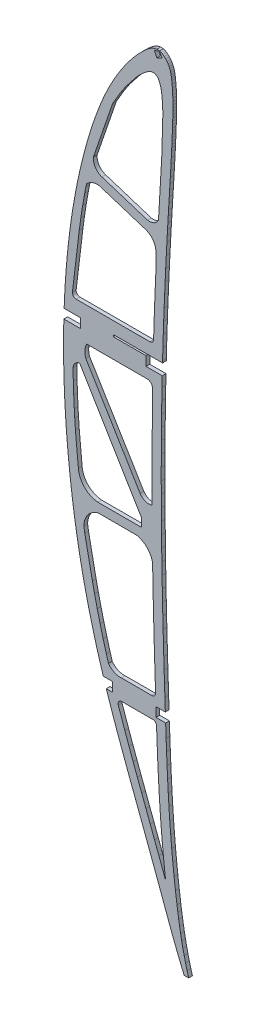
SolidWorks part; units mm, degrees
ref_plane "前视基准面" through (0, 0, 0) normal (0, 0, 1) x (1, 0, 0)
ref_plane "上视基准面" through (0, 0, 0) normal (0, 1, 0) x (1, 0, 0)
ref_plane "右视基准面" through (0, 0, 0) normal (1, 0, 0) x (0, 0, -1)
sketch "Model" plane through (0, 0, 0) normal (0, 0, 1) x (1, 0, 0)
  line L0 (90.473, 1.4161) -> (89.2536, 4.2882)
  line L1 (89.2536, 4.2882) -> (87.9798, 7.3505)
  line L2 (87.9798, 7.3505) -> (86.7325, 10.425)
  line L3 (86.7325, 10.425) -> (85.5328, 13.4636)
  line L4 (85.5328, 13.4636) -> (84.3598, 16.5103)
  line L5 (84.3598, 16.5103) -> (83.2074, 19.565)
  line L6 (83.2074, 19.565) -> (82.0699, 22.6253)
  line L7 (82.0699, 22.6253) -> (80.9421, 25.69)
  line L8 (80.9421, 25.69) -> (78.6963, 31.8259)
  line L9 (78.6963, 31.8259) -> (76.4399, 37.9543)
  line L10 (76.4399, 37.9543) -> (74.1677, 44.075)
  line L11 (74.1677, 44.075) -> (71.8829, 50.1892)
  line L12 (71.8829, 50.1892) -> (69.5892, 56.2989)
  line L13 (69.5892, 56.2989) -> (67.2905, 62.4075)
  line L14 (67.2905, 62.4075) -> (64.9878, 68.5169)
  line L15 (64.9878, 68.5169) -> (62.687, 74.6293)
  line L16 (62.687, 74.6293) -> (60.4035, 80.7125)
  line L17 (60.4035, 80.7125) -> (58.1378, 86.8005)
  line L18 (58.1378, 86.8005) -> (55.8997, 92.8976)
  line L19 (55.8997, 92.8976) -> (53.7021, 99.0086)
  line L20 (53.7021, 99.0086) -> (51.5567, 105.1368)
  line L21 (51.5567, 105.1368) -> (48.7789, 113.4293)
  line L22 (47.169, 118.4293) -> (45.5864, 123.5389)
  line L23 (45.5864, 123.5389) -> (43.7907, 129.6364)
  line L24 (43.7907, 129.6364) -> (42.081, 135.7577)
  line L25 (42.081, 135.7577) -> (40.4605, 141.9028)
  line L26 (40.4605, 141.9028) -> (38.9279, 148.0709)
  line L27 (38.9279, 148.0709) -> (37.4875, 154.2619)
  line L28 (37.4875, 154.2619) -> (36.1382, 160.475)
  line L29 (36.1382, 160.475) -> (34.9017, 166.6049)
  line L30 (34.9017, 166.6049) -> (33.7535, 172.7496)
  line L31 (33.7535, 172.7496) -> (32.6908, 178.9101)
  line L32 (32.6908, 178.9101) -> (31.7116, 185.0833)
  line L33 (31.7116, 185.0833) -> (30.8129, 191.269)
  line L34 (30.8129, 191.269) -> (29.9918, 197.4671)
  line L35 (29.9918, 197.4671) -> (29.2462, 203.6765)
  line L36 (29.2462, 203.6765) -> (28.5771, 209.8562)
  line L37 (28.5771, 209.8562) -> (27.9817, 216.0411)
  line L38 (27.9817, 216.0411) -> (27.4592, 222.2302)
  line L39 (27.4592, 222.2302) -> (27.0106, 228.4255)
  line L40 (27.0106, 228.4255) -> (26.6368, 234.6261)
  line L41 (26.6368, 234.6261) -> (26.3398, 240.8321)
  line L42 (26.3398, 240.8321) -> (26.1187, 247.0423)
  line L43 (26.1187, 247.0423) -> (25.9752, 253.264)
  line L44 (25.9752, 253.264) -> (25.9097, 259.485)
  line L45 (25.9097, 259.485) -> (25.9264, 265.7057)
  line L46 (25.9264, 265.7057) -> (26.0242, 271.9249)
  line L47 (26.0242, 271.9249) -> (26.0682, 273.4293)
  line L48 (26.2185, 278.4293) -> (26.4742, 284.3603)
  line L49 (26.4742, 284.3603) -> (26.8295, 290.5758)
  line L50 (26.8295, 290.5758) -> (27.2798, 296.8594)
  line L51 (27.2798, 296.8594) -> (27.8256, 303.1352)
  line L52 (27.8256, 303.1352) -> (28.4699, 309.3992)
  line L53 (28.4699, 309.3992) -> (29.219, 315.6509)
  line L54 (29.219, 315.6509) -> (30.0758, 321.8872)
  line L55 (30.0758, 321.8872) -> (31.0464, 328.1074)
  line L56 (31.0464, 328.1074) -> (32.1349, 334.3098)
  line L57 (32.1349, 334.3098) -> (32.7366, 337.4701)
  line L58 (32.7366, 337.4701) -> (33.3707, 340.6227)
  line L59 (33.3707, 340.6227) -> (34.0381, 343.7678)
  line L60 (34.0381, 343.7678) -> (34.7369, 346.9063)
  line L61 (34.7369, 346.9063) -> (35.47, 350.0362)
  line L62 (35.47, 350.0362) -> (36.2365, 353.1597)
  line L63 (36.2365, 353.1597) -> (37.0384, 356.2756)
  line L64 (37.0384, 356.2756) -> (37.8971, 359.4651)
  line L65 (37.8971, 359.4651) -> (38.7943, 362.6432)
  line L66 (38.7943, 362.6432) -> (39.7331, 365.8092)
  line L67 (39.7331, 365.8092) -> (40.7155, 368.9621)
  line L68 (40.7155, 368.9621) -> (41.7446, 372.0999)
  line L69 (41.7446, 372.0999) -> (42.8225, 375.2219)
  line L70 (42.8225, 375.2219) -> (43.952, 378.3282)
  line L71 (43.952, 378.3282) -> (44.5597, 379.9322)
  line L72 (44.5597, 379.9322) -> (45.1815, 381.5308)
  line L73 (45.1815, 381.5308) -> (45.8197, 383.1222)
  line L74 (45.8197, 383.1222) -> (46.4752, 384.7063)
  line L75 (46.4752, 384.7063) -> (47.1482, 386.2811)
  line L76 (47.1482, 386.2811) -> (47.8385, 387.8477)
  line L77 (47.8385, 387.8477) -> (48.5493, 389.4042)
  line L78 (48.5493, 389.4042) -> (49.3153, 391.0262)
  line L79 (49.3153, 391.0262) -> (50.1038, 392.6361)
  line L80 (50.1038, 392.6361) -> (50.9168, 394.2361)
  line L81 (50.9168, 394.2361) -> (51.7533, 395.8241)
  line L82 (51.7533, 395.8241) -> (52.6142, 397.4041)
  line L83 (52.6142, 397.4041) -> (53.5026, 398.9744)
  line L84 (53.5026, 398.9744) -> (54.4183, 400.5368)
  line L85 (54.4183, 400.5368) -> (55.4371, 402.2139)
  line L86 (55.4371, 402.2139) -> (56.4875, 403.8773)
  line L87 (56.4875, 403.8773) -> (57.565, 405.5178)
  line L88 (57.565, 405.5178) -> (58.6677, 407.1315)
  line L89 (58.6677, 407.1315) -> (59.7948, 408.7121)
  line L90 (59.7948, 408.7121) -> (60.9427, 410.2527)
  line L91 (60.9427, 410.2527) -> (62.1106, 411.748)
  line L92 (62.1106, 411.748) -> (62.8372, 412.6426)
  line L93 (62.8372, 412.6426) -> (63.5775, 413.5247)
  line L94 (63.5775, 413.5247) -> (64.336, 414.3996)
  line L95 (64.336, 414.3996) -> (65.1196, 415.2756)
  line L96 (65.1196, 415.2756) -> (65.9348, 416.159)
  line L97 (65.9348, 416.159) -> (66.7875, 417.0561)
  line L98 (66.7875, 417.0561) -> (67.6853, 417.9731)
  line L99 (67.6853, 417.9731) -> (68.9368, 419.2049)
  line L100 (68.9368, 419.2049) -> (70.2576, 420.4066)
  line L101 (70.2576, 420.4066) -> (71.6302, 421.5015)
  line L102 (71.6302, 421.5015) -> (73.0377, 422.4138)
  line L103 (73.0377, 422.4138) -> (74.4616, 423.0665)
  line L104 (74.4616, 423.0665) -> (75.8862, 423.383)
  line L105 (75.8862, 423.383) -> (77.2927, 423.2862)
  line L106 (77.2927, 423.2862) -> (78.1436, 422.9933)
  line L107 (78.1436, 422.9933) -> (78.1545, 422.9896)
  line L108 (78.1545, 422.9896) -> (78.9905, 422.5256)
  line L109 (78.9905, 422.5256) -> (79.7866, 421.9227)
  line L110 (79.7866, 421.9227) -> (80.5307, 421.2035)
  line L111 (80.5307, 421.2035) -> (81.2106, 420.3954)
  line L112 (81.2106, 420.3954) -> (81.8132, 419.5228)
  line L113 (81.8132, 419.5228) -> (82.3264, 418.6124)
  line L114 (82.3264, 418.6124) -> (82.6997, 417.7879)
  line L115 (82.6997, 417.7879) -> (83.0023, 416.9553)
  line L116 (83.0023, 416.9553) -> (83.2442, 416.115)
  line L117 (83.2442, 416.115) -> (83.4364, 415.2676)
  line L118 (83.4364, 415.2676) -> (83.5887, 414.4144)
  line L119 (83.5887, 414.4144) -> (83.7122, 413.557)
  line L120 (83.7122, 413.557) -> (83.8159, 412.6957)
  line L121 (83.8159, 412.6957) -> (83.9762, 411.1562)
  line L122 (83.9762, 411.1562) -> (84.1087, 409.6125)
  line L123 (84.1087, 409.6125) -> (84.2163, 408.0638)
  line L124 (84.2163, 408.0638) -> (84.2991, 406.5119)
  line L125 (84.2991, 406.5119) -> (84.36, 404.9571)
  line L126 (84.36, 404.9571) -> (84.3999, 403.4013)
  line L127 (84.3999, 403.4013) -> (84.4207, 401.8468)
  line L128 (84.4207, 401.8468) -> (84.4237, 400.2884)
  line L129 (84.4237, 400.2884) -> (84.4105, 398.7323)
  line L130 (84.4105, 398.7323) -> (84.3833, 397.1777)
  line L131 (84.3833, 397.1777) -> (84.3451, 395.6225)
  line L132 (84.3451, 395.6225) -> (84.2988, 394.069)
  line L133 (84.2988, 394.069) -> (84.2456, 392.5152)
  line L134 (84.2456, 392.5152) -> (84.1873, 390.9602)
  line L135 (84.1873, 390.9602) -> (84.1282, 389.4032)
  line L136 (84.1282, 389.4032) -> (84.066, 387.847)
  line L137 (84.066, 387.847) -> (84.0018, 386.2907)
  line L138 (84.0018, 386.2907) -> (83.9357, 384.7343)
  line L139 (83.9357, 384.7343) -> (83.8665, 383.1778)
  line L140 (83.8665, 383.1778) -> (83.7943, 381.6212)
  line L141 (83.7943, 381.6212) -> (83.7202, 380.0645)
  line L142 (83.7202, 380.0645) -> (83.562, 376.9476)
  line L143 (83.562, 376.9476) -> (83.3927, 373.8313)
  line L144 (83.3927, 373.8313) -> (83.2164, 370.7166)
  line L145 (83.2164, 370.7166) -> (83.0321, 367.6026)
  line L146 (83.0321, 367.6026) -> (82.8447, 364.4885)
  line L147 (82.8447, 364.4885) -> (82.6544, 361.3742)
  line L148 (82.6544, 361.3742) -> (82.4641, 358.2589)
  line L149 (82.4641, 358.2589) -> (82.2749, 355.1427)
  line L150 (82.2749, 355.1427) -> (82.0876, 352.0276)
  line L151 (82.0876, 352.0276) -> (81.9022, 348.9135)
  line L152 (81.9022, 348.9135) -> (81.7209, 345.7986)
  line L153 (81.7209, 345.7986) -> (81.5416, 342.6839)
  line L154 (81.5416, 342.6839) -> (81.3663, 339.5683)
  line L155 (81.3663, 339.5683) -> (81.1941, 336.4518)
  line L156 (81.1941, 336.4518) -> (80.8634, 330.2254)
  line L157 (80.8634, 330.2254) -> (80.5506, 324.0009)
  line L158 (80.5506, 324.0009) -> (80.2548, 317.776)
  line L159 (80.2548, 317.776) -> (79.9771, 311.551)
  line L160 (79.9771, 311.551) -> (79.7175, 305.3237)
  line L161 (79.7175, 305.3237) -> (79.4779, 299.0954)
  line L162 (79.4779, 299.0954) -> (79.2585, 292.8649)
  line L163 (79.2585, 292.8649) -> (79.0597, 286.6443)
  line L164 (79.0597, 286.6443) -> (78.8818, 280.4246)
  line L165 (78.8818, 280.4246) -> (78.8564, 279.4293)
  line L166 (78.7057, 273.4293) -> (78.5851, 267.9858)
  line L167 (78.5851, 267.9858) -> (78.4673, 261.7657)
  line L168 (78.4673, 261.7657) -> (78.3696, 255.5436)
  line L169 (78.3696, 255.5436) -> (78.292, 249.3203)
  line L170 (78.292, 249.3203) -> (78.2341, 243.1038)
  line L171 (78.2341, 243.1038) -> (78.1961, 236.8892)
  line L172 (78.1961, 236.8892) -> (78.1771, 230.6755)
  line L173 (78.1771, 230.6755) -> (78.1751, 224.4625)
  line L174 (78.1751, 224.4625) -> (78.1912, 218.2483)
  line L175 (78.1912, 218.2483) -> (78.2233, 212.0338)
  line L176 (78.2233, 212.0338) -> (78.2715, 205.817)
  line L177 (78.2715, 205.817) -> (78.3346, 199.6048)
  line L178 (78.3346, 199.6048) -> (78.4125, 193.3943)
  line L179 (78.4125, 193.3943) -> (78.5045, 187.1844)
  line L180 (78.5045, 187.1844) -> (78.6114, 180.9761)
  line L181 (78.6114, 180.9761) -> (78.7323, 174.7675)
  line L182 (78.7323, 174.7675) -> (78.8663, 168.5574)
  line L183 (78.8663, 168.5574) -> (79.0144, 162.347)
  line L184 (79.0144, 162.347) -> (79.1754, 156.1381)
  line L185 (79.1754, 156.1381) -> (79.3482, 149.9317)
  line L186 (79.3482, 149.9317) -> (79.5311, 143.7268)
  line L187 (79.5311, 143.7268) -> (79.7239, 137.5213)
  line L188 (79.7239, 137.5213) -> (79.9228, 131.3171)
  line L189 (79.9228, 131.3171) -> (80.1297, 125.1102)
  line L190 (80.1297, 125.1102) -> (80.3571, 118.4293)
  line L191 (80.5289, 113.4293) -> (80.7816, 106.4889)
  line L192 (80.7816, 106.4889) -> (81.0244, 100.2856)
  line L193 (81.0244, 100.2856) -> (81.2912, 94.0833)
  line L194 (81.2912, 94.0833) -> (81.5889, 87.8834)
  line L195 (81.5889, 87.8834) -> (81.9236, 81.6841)
  line L196 (81.9236, 81.6841) -> (82.3043, 75.4858)
  line L197 (82.3043, 75.4858) -> (82.7354, 69.2817)
  line L198 (82.7354, 69.2817) -> (83.2212, 63.083)
  line L199 (83.2212, 63.083) -> (83.7659, 56.8899)
  line L200 (83.7659, 56.8899) -> (84.3733, 50.7025)
  line L201 (84.3733, 50.7025) -> (85.0457, 44.5199)
  line L202 (85.0457, 44.5199) -> (85.7878, 38.3434)
  line L203 (85.7878, 38.3434) -> (86.6038, 32.1711)
  line L204 (86.6038, 32.1711) -> (87.0437, 29.0654)
  line L205 (87.0437, 29.0654) -> (87.5093, 25.9657)
  line L206 (87.5093, 25.9657) -> (88.0068, 22.8715)
  line L207 (88.0068, 22.8715) -> (88.5429, 19.7849)
  line L208 (88.5429, 19.7849) -> (89.1227, 16.7073)
  line L209 (89.1227, 16.7073) -> (89.7531, 13.6409)
  line L210 (89.7531, 13.6409) -> (90.4399, 10.5869)
  line L211 (90.4399, 10.5869) -> (91.2028, 7.4882)
  line L212 (91.2028, 7.4882) -> (92.0221, 4.404)
  line L213 (92.0221, 4.404) -> (92.864, 1.4161)
  line L214 (92.864, 1.4161) -> (90.473, 1.4161)
  line L215 (75.3292, 320.7533) -> (75.0514, 314.5283)
  line L216 (75.0514, 314.5283) -> (74.7918, 308.301)
  line L217 (74.7918, 308.301) -> (74.5523, 302.0726)
  line L218 (74.5523, 302.0726) -> (74.3328, 295.8421)
  line L219 (74.3328, 295.8421) -> (74.134, 289.6216)
  line L220 (74.134, 289.6216) -> (74.0833, 287.8494)
  line L221 (72.0841, 285.9066) -> (32.6268, 285.9066)
  line L222 (30.641, 288.1445) -> (34.2933, 318.6281)
  line L223 (34.2933, 318.6281) -> (35.1501, 324.8644)
  line L224 (35.1501, 324.8644) -> (36.1207, 331.0847)
  line L225 (36.1207, 331.0847) -> (37.2092, 337.2871)
  line L226 (37.2092, 337.2871) -> (37.8109, 340.4473)
  line L227 (31.8893, 230.4372) -> (31.6368, 234.6261)
  line L228 (31.6368, 234.6261) -> (31.3398, 240.8321)
  line L229 (31.3398, 240.8321) -> (31.1187, 247.0423)
  line L230 (31.1187, 247.0423) -> (30.9752, 253.264)
  line L231 (57.1011, 111.6348) -> (73.6657, 111.6348)
  line L232 (75.6644, 109.7076) -> (75.7816, 106.4889)
  line L233 (75.7816, 106.4889) -> (76.0244, 100.2856)
  line L234 (76.0244, 100.2856) -> (76.2912, 94.0833)
  line L235 (76.2912, 94.0833) -> (76.5889, 87.8834)
  line L236 (76.5889, 87.8834) -> (76.9236, 81.6841)
  line L237 (76.9236, 81.6841) -> (77.3043, 75.4858)
  line L238 (77.3043, 75.4858) -> (77.7354, 69.2817)
  line L239 (77.7354, 69.2817) -> (78.2212, 63.083)
  line L240 (78.2212, 63.083) -> (78.7659, 56.8899)
  line L241 (78.7659, 56.8899) -> (79.3733, 50.7025)
  line L242 (79.3733, 50.7025) -> (80.0457, 44.5199)
  line L243 (80.0457, 44.5199) -> (80.5449, 40.3653)
  line L244 (80.5449, 40.3653) -> (79.1677, 44.075)
  line L245 (79.1677, 44.075) -> (76.8829, 50.1892)
  line L246 (76.8829, 50.1892) -> (74.5892, 56.2989)
  line L247 (74.5892, 56.2989) -> (72.2905, 62.4075)
  line L248 (72.2905, 62.4075) -> (69.9878, 68.5169)
  line L249 (69.9878, 68.5169) -> (67.687, 74.6293)
  line L250 (67.687, 74.6293) -> (65.4035, 80.7125)
  line L251 (65.4035, 80.7125) -> (63.1378, 86.8005)
  line L252 (63.1378, 86.8005) -> (60.8997, 92.8976)
  line L253 (60.8997, 92.8976) -> (58.7021, 99.0086)
  line L254 (58.7021, 99.0086) -> (55.2134, 108.974)
  line L255 (49.9336, 125.7554) -> (48.7907, 129.6364)
  line L256 (48.7907, 129.6364) -> (47.081, 135.7577)
  line L257 (47.081, 135.7577) -> (45.4605, 141.9028)
  line L258 (45.4605, 141.9028) -> (43.9279, 148.0709)
  line L259 (43.9279, 148.0709) -> (42.4875, 154.2619)
  line L260 (42.4875, 154.2619) -> (41.3223, 159.6277)
  line L261 (26.2185, 278.4293) -> (33.8514, 278.4293)
  line L262 (47.169, 118.4293) -> (52.169, 118.4293)
  line L263 (52.169, 118.4293) -> (52.169, 113.4293)
  line L264 (52.169, 113.4293) -> (48.7789, 113.4293)
  line L265 (75.3571, 118.4293) -> (75.3571, 113.4293)
  line L266 (75.3571, 118.4293) -> (80.3571, 118.4293)
  line L267 (80.5289, 113.4293) -> (75.3571, 113.4293)
  line L268 (70.057, 278.4293) -> (52.5208, 278.4293)
  line L269 (52.5208, 278.4293) -> (52.5208, 279.4293)
  line L270 (52.5208, 279.4293) -> (78.8564, 279.4293)
  line L271 (46.4432, 349.4196) -> (70.7733, 341.6607)
  line L272 (44.9904, 344.6799) -> (69.9353, 336.7249)
  line L273 (77.2787, 423.2659) -> (74.5538, 422.0128)
  line L274 (74.5538, 422.0128) -> (75.8059, 419.2879)
  line L275 (75.8059, 419.2879) -> (78.5318, 420.54)
  line L276 (78.5318, 420.54) -> (77.2787, 423.2659)
  line L277 (70.057, 273.4293) -> (70.057, 278.4293)
  line L278 (34.8514, 273.4293) -> (34.8514, 278.4293)
  line L279 (34.8514, 278.4293) -> (33.8514, 278.4293)
  line L280 (31.8893, 230.4372) -> (32.2643, 224.8927)
  line L282 (73.1408, 122.4795) -> (56.8453, 122.4795)
  line L283 (73.5404, 184.322) -> (73.6114, 180.9761)
  line L284 (73.6114, 180.9761) -> (73.7323, 174.7675)
  line L285 (73.7323, 174.7675) -> (73.8663, 168.5574)
  line L286 (73.8663, 168.5574) -> (74.0144, 162.347)
  line L287 (74.0144, 162.347) -> (74.1754, 156.1381)
  line L288 (74.1754, 156.1381) -> (74.5473, 142.7867)
  line L289 (34.8514, 273.4293) -> (26.0682, 273.4293)
  line L290 (70.057, 273.4293) -> (78.7057, 273.4293)
  line L291 (32.2643, 224.8927) -> (33.8226, 208.1791)
  line L292 (73.4184, 258.6547) -> (73.2137, 210.769)
  line L293 (74.5473, 142.7867) -> (75.1398, 124.5435)
  line L294 (37.2459, 179.7701) -> (41.3223, 159.6277)
  line L295 (38.2602, 342.1884) -> (37.8109, 340.4473)
  line L296 (75.3159, 329.6589) -> (75.3292, 320.7533)
  line L297 (67.6008, 197.6192) -> (44.2699, 197.6192)
  line L298 (36.7734, 182.7617) -> (37.2459, 179.7701)
  line L299 (64.9655, 192.7153) -> (44.3652, 192.7153)
  line L300 (34.5066, 257.2134) -> (67.6008, 202.1558)
  line L301 (66.8738, 212.9825) -> (37.8446, 260.9465)
  line L302 (67.6008, 197.6192) -> (67.6008, 202.1558)
  line L303 (38.2707, 267.9293) -> (70.5267, 267.9293)
  line L304 (73.4184, 258.6547) -> (73.5261, 264.8725)
  line L305 (52.1481, 386.2812) -> (56.2281, 393.2422)
  line L306 (56.2281, 393.2422) -> (59.4381, 398.0562)
  line L307 (59.4381, 398.0562) -> (64.7579, 404.7783)
  line L308 (64.7579, 404.7783) -> (66.3781, 406.5212)
  line L309 (66.3781, 406.5212) -> (67.4881, 407.6302)
  line L310 (67.4881, 407.6302) -> (69.2977, 409.2648)
  line L311 (69.2977, 409.2648) -> (70.9081, 410.4512)
  line L312 (70.9081, 410.4512) -> (71.8781, 411.0142)
  line L313 (71.8781, 411.0142) -> (73.2081, 411.5292)
  line L314 (73.2081, 411.5292) -> (74.821, 411.5261)
  line L315 (74.821, 411.5261) -> (76.2702, 410.5643)
  line L316 (76.2702, 410.5643) -> (76.6922, 409.9788)
  line L317 (76.6922, 409.9788) -> (77.3781, 408.5462)
  line L318 (77.3781, 408.5462) -> (77.8181, 407.2012)
  line L319 (77.8181, 407.2012) -> (78.2381, 405.3162)
  line L320 (78.2381, 405.3162) -> (78.6081, 402.7772)
  line L321 (78.6081, 402.7772) -> (78.9181, 398.5922)
  line L322 (78.9181, 398.5922) -> (78.9681, 397.2252)
  line L323 (78.9681, 397.2252) -> (78.9981, 396.2892)
  line L324 (78.9981, 396.2892) -> (79.0181, 394.3582)
  line L325 (79.0181, 394.3582) -> (78.4581, 374.9882)
  line L326 (52.1481, 386.2812) -> (41.8881, 356.4322)
  line L327 (76.6981, 344.4732) -> (78.4581, 374.9882)
  arc A0 (41.8881, 356.4322) -> (46.4432, 349.4196) centre (48.4515, 355.7099) ccw
  arc A1 (44.9904, 344.6799) -> (38.2602, 342.1884) centre (44.0327, 336.9311) ccw
  arc A2 (70.7733, 341.6607) -> (76.6981, 344.4732) centre (71.877, 346.9824) ccw
  arc A3 (75.3159, 329.6589) -> (69.9353, 336.7249) centre (67.265, 329.11) ccw
  arc A4 (33.8226, 208.1791) -> (44.2699, 197.6192) centre (45.1486, 208.9364) ccw
  arc A5 (44.3652, 192.7153) -> (36.7734, 182.7617) centre (47.1471, 182.7214) ccw
  arc A6 (73.5404, 184.322) -> (64.9655, 192.7153) centre (62.8801, 182.0078) ccw
  arc A7 (66.8738, 212.9825) -> (73.2137, 210.769) centre (71.3745, 215.6875) ccw
  arc A8 (38.2707, 267.9293) -> (37.8446, 260.9465) centre (46.3986, 263.929) ccw
  arc A9 (34.5066, 257.2134) -> (30.9752, 253.264) centre (35.2868, 252.9621) ccw
  arc A10 (73.5261, 264.8725) -> (70.5267, 267.9293) centre (70.5267, 264.9293) ccw
  arc A11 (49.9336, 125.7554) -> (56.8453, 122.4795) centre (56.2435, 130.1391) ccw
  arc A12 (72.0841, 285.9066) -> (74.0833, 287.8494) centre (72.0841, 287.9066) ccw
  arc A13 (30.641, 288.1445) -> (32.6268, 285.9066) centre (32.6268, 287.9066) ccw
  arc A14 (57.1011, 111.6348) -> (55.2134, 108.974) centre (57.1011, 109.6348) ccw
  arc A15 (75.6644, 109.7076) -> (73.6657, 111.6348) centre (73.6657, 109.6348) ccw
  arc A16 (73.1408, 122.4795) -> (75.1398, 124.5435) centre (73.1408, 124.4795) ccw
extrude "凸台-拉伸1" add sketch "Model" along normal blind 2
